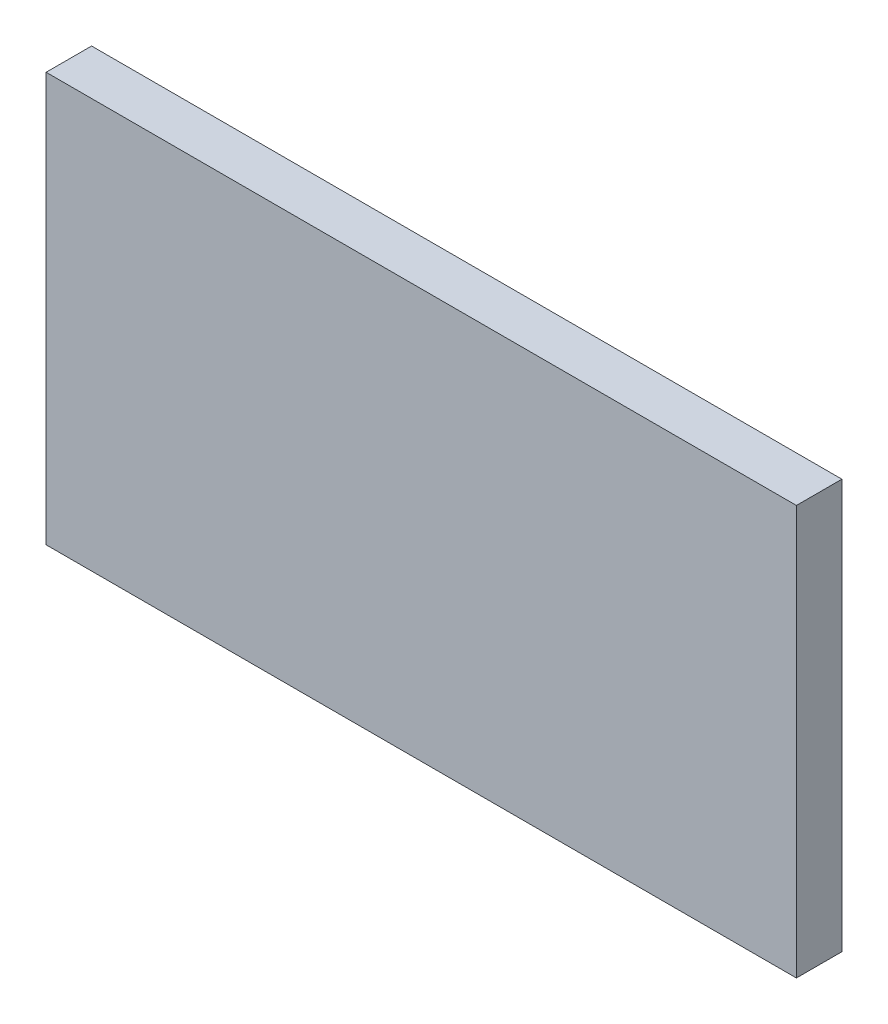
SolidWorks part; units mm, degrees
ref_plane "Front" through (0, 0, 0) normal (0, 0, 1) x (1, 0, 0)
ref_plane "Top" through (0, 0, 0) normal (0, 1, 0) x (1, 0, 0)
ref_plane "Right" through (0, 0, 0) normal (1, 0, 0) x (0, 0, -1)
sketch "Esquisse1" plane through (0, 0, 0) normal (0, 0, 1) x (1, 0, 0)
  line L1 (0, 0) -> (3300, 0)
  line L2 (0, 0) -> (0, 1800)
  line L3 (0, 1800) -> (3300, 1800)
  line L4 (3300, 0) -> (3300, 1800)
  dimension "D1" = 1800
  dimension "D2" = 3300
extrude "Boss.-Extru.1" add sketch "Esquisse1" along normal blind 200
